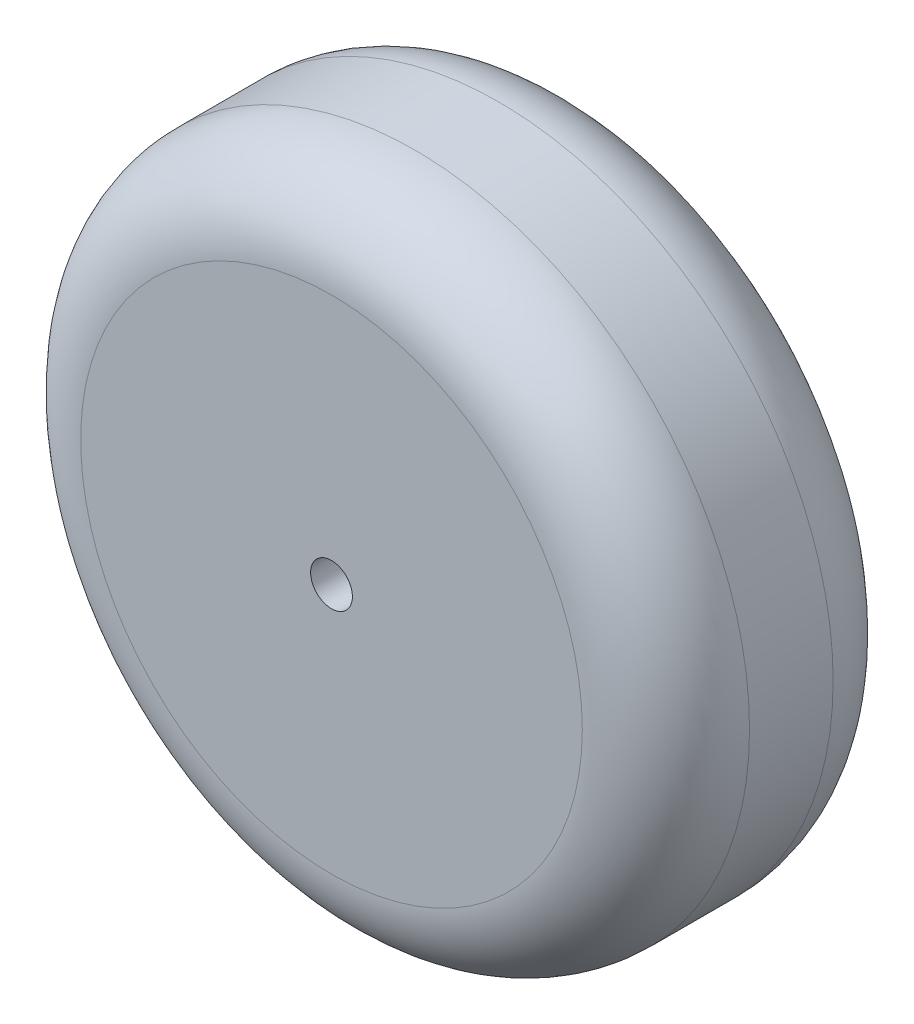
SolidWorks part; units mm, degrees
material "BUTYL"
ref_plane "Front Plane" through (0, 0, 0) normal (0, 0, 1) x (1, 0, 0)
ref_plane "Top Plane" through (0, 0, 0) normal (0, 1, 0) x (1, 0, 0)
ref_plane "Right Plane" through (0, 0, 0) normal (1, 0, 0) x (0, 0, -1)
sketch "Sketch1" plane through (0, 0, 0) normal (0, 0, 1) x (1, 0, 0)
  circle A0 centre (0, 0) radius 40
  dimension "D1" = 80
extrude "Boss-Extrude1" add sketch "Sketch1" along normal blind 30
fillet "Fillet1" radius 10 2 edges at (40, 0, 0) (40, 0, 30)
sketch "Sketch2" plane through (0, 0, 30) normal (0, 0, 1) x (1, 0, 0)
  circle A0 centre (0, 0) radius 2.5
  dimension "D1" = 5
extrude "Cut-Extrude1" cut sketch "Sketch2" against normal blind 30
